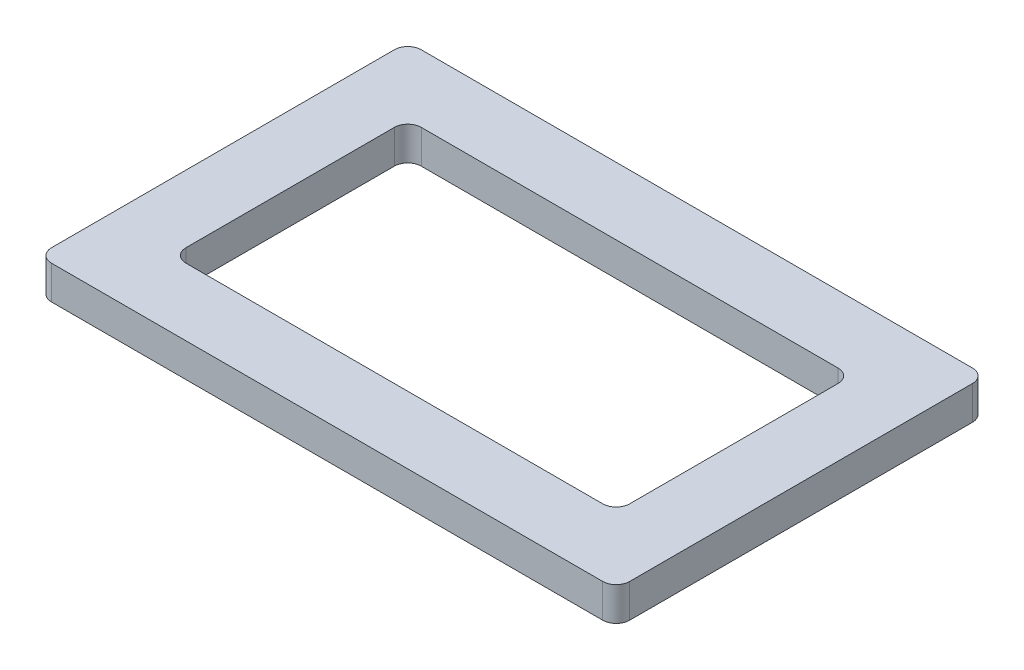
SolidWorks part; units mm, degrees
ref_plane "Front" through (0, 0, 0) normal (0, 0, 1) x (1, 0, 0)
ref_plane "Top" through (0, 0, 0) normal (0, 1, 0) x (1, 0, 0)
ref_plane "Right" through (0, 0, 0) normal (1, 0, 0) x (0, 0, -1)
sketch "Sketch1" plane through (0, 0, 0) normal (0, 1, 0) x (1, 0, 0)
  line L1 (-43, -27.5) -> (43, -27.5)
  line L2 (-43, -27.5) -> (-43, 27.5)
  line L3 (-43, 27.5) -> (43, 27.5)
  line L4 (43, -27.5) -> (43, 27.5)
  line L5 (-43, -27.5) -> (43, 27.5) construction
  line L6 (-43, 27.5) -> (43, -27.5) construction
  point P0 (0, 0)
  dimension "D1" = 55
  dimension "D2" = 86
extrude "Boss-Extrude1" add sketch "Sketch1" along normal blind 5
sketch "Sketch2" plane through (0, 5, 0) normal (0, 1, 0) x (1, 0, 0)
  line L0 (43, -27.5) -> (43, 27.5) construction
  line L1 (-43, -27.5) -> (43, -27.5) construction
  circle A0 centre (19, -2.5) radius 7.5
  dimension "D3" = 15
  dimension "D1" = 24
  dimension "D2" = 25
extrude "Cut-Extrude1" cut sketch "Sketch2" against normal through all
sketch "Sketch3" plane through (0, 5, 0) normal (0, 1, 0) x (1, 0, 0)
  line L0 (43, 27.5) -> (-43, 27.5) construction
  line L1 (-33, -17.5) -> (33, -17.5)
  line L2 (-33, -17.5) -> (-33, 17.5)
  line L3 (-33, 17.5) -> (33, 17.5)
  line L4 (33, -17.5) -> (33, 17.5)
  line L5 (-33, -17.5) -> (33, 17.5) construction
  line L6 (-33, 17.5) -> (33, -17.5) construction
  line L7 (-43, 27.5) -> (-43, -27.5) construction
  point P0 (0, 0)
  dimension "D1" = 10
  dimension "D2" = 10
extrude "Cut-Extrude2" cut sketch "Sketch3" against normal through all
fillet "Fillet1" radius 2 8 edges at (33, 2.5, 17.5) (33, 2.5, -17.5) (-33, 2.5, 17.5) (-33, 2.5, -17.5) (43, 2.5, -27.5) (43, 2.5, 27.5) (-43, 2.5, -27.5) (-43, 2.5, 27.5)
